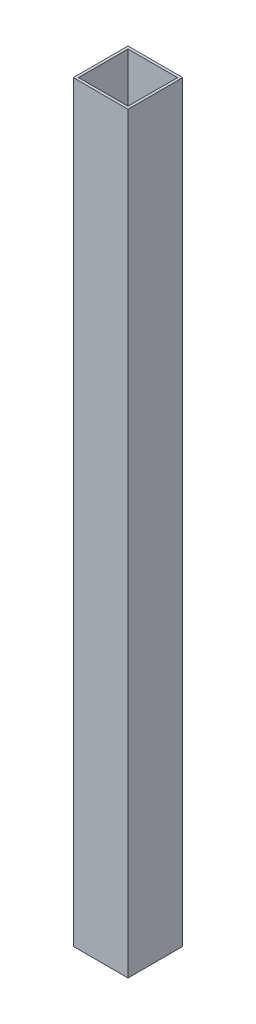
SolidWorks part; units mm, degrees
ref_plane "Front Plane" through (0, 0, 0) normal (0, 0, 1) x (1, 0, 0)
ref_plane "Top Plane" through (0, 0, 0) normal (0, 1, 0) x (1, 0, 0)
ref_plane "Right Plane" through (0, 0, 0) normal (1, 0, 0) x (0, 0, -1)
sketch "Sketch2" plane through (0, 0, 0) normal (0, 1, 0) x (1, 0, 0)
  line L0 (-11.5, 11.5) -> (11.5, 11.5)
  line L1 (-12.7, -12.7) -> (12.7, -12.7)
  line L2 (-12.7, -12.7) -> (-12.7, 12.7)
  line L3 (-12.7, 12.7) -> (12.7, 12.7)
  line L4 (12.7, -12.7) -> (12.7, 12.7)
  line L5 (-12.7, -12.7) -> (12.7, 12.7) construction
  line L6 (-12.7, 12.7) -> (12.7, -12.7) construction
  line L7 (11.5, -11.5) -> (11.5, 11.5)
  line L8 (-11.5, -11.5) -> (11.5, -11.5)
  line L9 (-11.5, -11.5) -> (-11.5, 11.5)
  point P0 (0, 0)
  dimension "D1" = 25.4
  dimension "D3" = 1.2
extrude "Boss-Extrude1" add sketch "Sketch2" along normal blind 349.2
